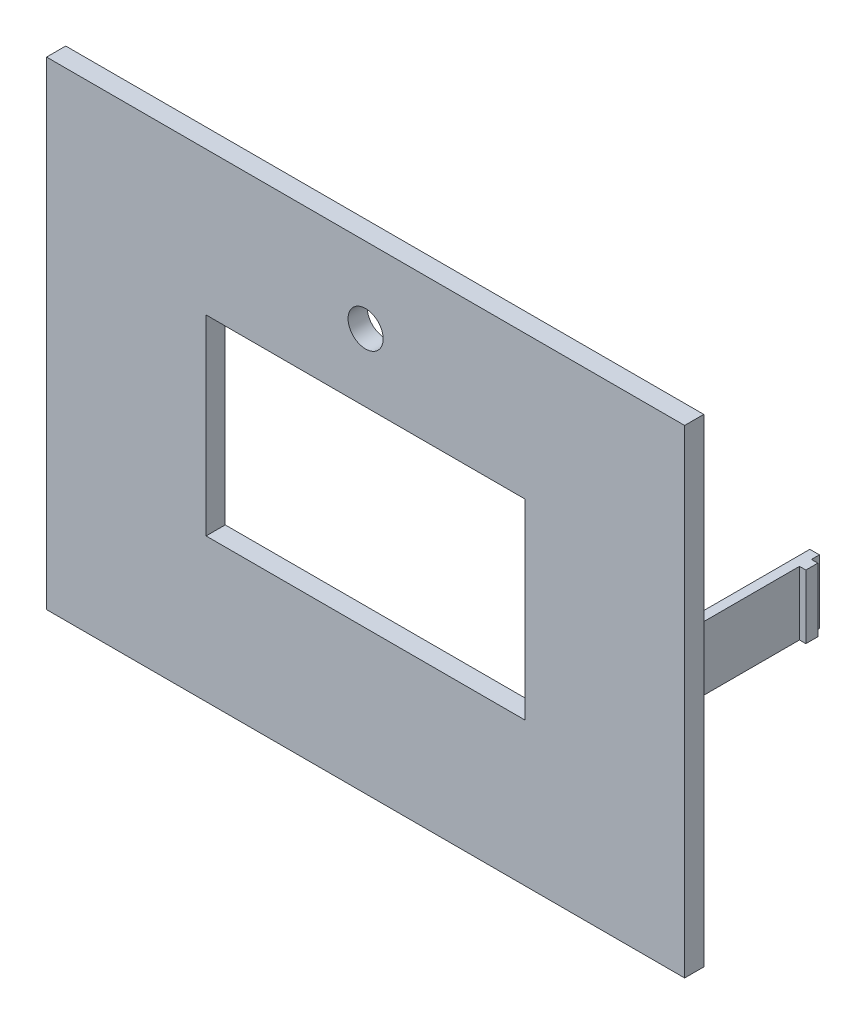
SolidWorks part; units mm, degrees
ref_plane "Front Plane" through (0, 0, 0) normal (0, 0, 1) x (1, 0, 0)
ref_plane "Top Plane" through (0, 0, 0) normal (0, 1, 0) x (1, 0, 0)
ref_plane "Right Plane" through (0, 0, 0) normal (1, 0, 0) x (0, 0, -1)
other "Configuration Table"
sketch "Sketch2" plane through (0, 0, 0) normal (0, 0, 1) x (1, 0, 0)
  line L1 (-40, -30) -> (40, -30)
  line L2 (-40, -30) -> (-40, 30)
  line L3 (-40, 30) -> (40, 30)
  line L4 (40, -30) -> (40, 30)
  line L5 (-20, -12) -> (20, -12)
  line L6 (-20, -12) -> (-20, 12)
  line L7 (-20, 12) -> (20, 12)
  line L8 (20, -12) -> (20, 12)
extrude "Lid_frame" add sketch "Sketch2" along normal blind 2.4 from offset 0
sketch "Sketch3" plane through (0, 0, 0) normal (0, 0, 1) x (1, 0, 0)
  line L1 (-36.5, -4) -> (-35.3, -4)
  line L2 (-36.5, -4) -> (-36.5, 4)
  line L3 (-36.5, 4) -> (-35.3, 4)
  line L4 (-35.3, -4) -> (-35.3, 4)
extrude "Snap_left" add sketch "Sketch3" along normal blind 18 from offset 18
sketch "Sketch4" plane through (0, 0, 0) normal (0, 0, 1) x (1, 0, 0)
  line L1 (35.3, -4) -> (36.5, -4)
  line L2 (35.3, -4) -> (35.3, 4)
  line L3 (35.3, 4) -> (36.5, 4)
  line L4 (36.5, -4) -> (36.5, 4)
extrude "Snap_right" add sketch "Sketch4" along normal blind 18 from offset 18
sketch "Sketch5" plane through (0, 0, 0) normal (0, 0, 1) x (1, 0, 0)
  line L1 (-37.3, -4) -> (-36.5, -4)
  line L2 (-37.3, -4) -> (-37.3, 4)
  line L3 (-37.3, 4) -> (-36.5, 4)
  line L4 (-36.5, -4) -> (-36.5, 4)
extrude "Hook_left" add sketch "Sketch5" along normal blind 1.5 from offset 17
sketch "Sketch6" plane through (0, 0, 0) normal (0, 0, 1) x (1, 0, 0)
  line L1 (36.5, -4) -> (37.3, -4)
  line L2 (36.5, -4) -> (36.5, 4)
  line L3 (36.5, 4) -> (37.3, 4)
  line L4 (37.3, -4) -> (37.3, 4)
extrude "Hook_right" add sketch "Sketch6" along normal blind 1.5 from offset 17
sketch "Sketch7" plane through (0, 0, 0) normal (0, 0, 1) x (1, 0, 0)
  circle A0 centre (0, 20.5) radius 2.2
sketch "Sketch8" plane through (0, 0, 0) normal (0, 0, 1) x (1, 0, 0)
  circle A0 centre (0, 20.5) radius 2.2
extrude "Shaft_clearance_D4p4" cut sketch "Sketch8" along normal through all
